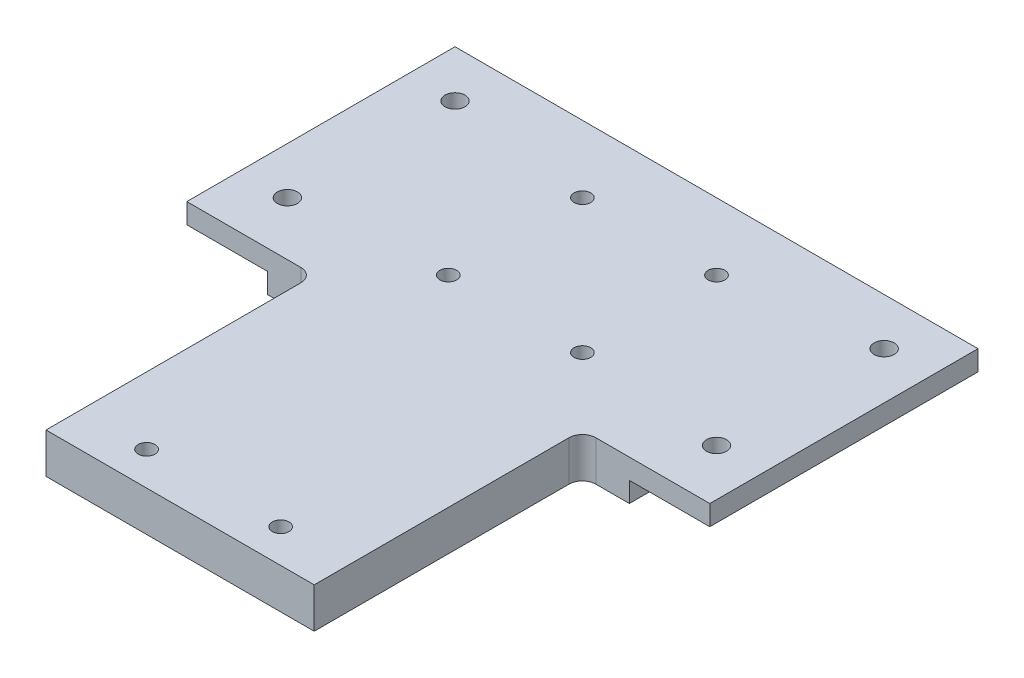
SolidWorks part; units mm, degrees
material "AISI 1045 钢，冷拔"
ref_plane "前视基准面" through (0, 0, 0) normal (0, 0, 1) x (1, 0, 0)
ref_plane "上视基准面" through (0, 0, 0) normal (0, 1, 0) x (1, 0, 0)
ref_plane "右视基准面" through (0, 0, 0) normal (1, 0, 0) x (0, 0, -1)
sketch "草图1" plane through (0, 0, 0) normal (0, 1, 0) x (1, 0, 0)
  line L0 (20, 0) -> (20, 82) construction
  line L1 (0, 0) -> (40, 0)
  line L7 (-19, 80) -> (-19, 40)
  line L8 (-19, 40) -> (0, 40)
  line L9 (0, 40) -> (0, 0)
  line L12 (59, 80) -> (59, 40)
  line L13 (59, 40) -> (40, 40)
  line L14 (40, 40) -> (40, 0)
  line L15 (-19, 80) -> (59, 80)
  dimension "D3" = 80
  dimension "D1" = 40
  dimension "D2" = 78
  dimension "D9" = 40
extrude "凸台-拉伸1" add sketch "草图1" along normal blind 6
fillet "圆角1" radius 2 2 edges at (0, 3, -40) (40, 3, -40)
sketch "草图18" plane through (0, 0, 0) normal (0, -1, 0) x (1, 0, 0)
  line L0 (-19, -40) -> (-7, -40)
  line L1 (-19, -40) -> (-2, -40) construction
  line L2 (-7, -40) -> (-7, -80)
  line L3 (59, -80) -> (-19, -80) construction
  line L4 (-7, -80) -> (-19, -80)
  line L5 (-19, -80) -> (-19, -40)
  line L6 (20, -80) -> (20, -16.0462) construction
  line L7 (47, -80) -> (59, -80)
  line L8 (59, -80) -> (59, -40)
  line L9 (59, -40) -> (47, -40)
  line L10 (47, -40) -> (47, -80)
  dimension "D1" = 12
extrude "切除-拉伸7" cut sketch "草图18" against normal blind 3
sketch "草图19" plane through (0, 3, 0) normal (0, -1, 0) x (1, 0, 0)
  line L0 (-19, -80) -> (-7, -80) construction
  line L1 (-19, -40) -> (-19, -80) construction
  line L2 (20, -91.1529) -> (20, -9.167) construction
  circle A0 centre (-12, -48) radius 1.5
  circle A1 centre (-12, -73) radius 1.5
  circle A2 centre (52, -73) radius 1.5
  circle A3 centre (52, -48) radius 1.5
  point P11 (30.8615, -109.7871)
  dimension "D2" = 3
  dimension "D1" = 7
  dimension "D3" = 25
  dimension "D4" = 7
  dimension "D5" = 39
extrude "切除-拉伸8" cut sketch "草图19" against normal blind 10
sketch "草图20" plane through (0, 0, 0) normal (0, -1, 0) x (1, 0, 0)
  line L0 (20, 0) -> (20, -11.5789) construction
  line L1 (0, 0) -> (40, 0) construction
  line L2 (47, -80) -> (-7, -80) construction
  circle A0 centre (10, -5) radius 1.25
  circle A1 centre (30, -5) radius 1.25
  circle A2 centre (10, -50) radius 1.25
  circle A3 centre (10, -70) radius 1.25
  circle A4 centre (30, -50) radius 1.25
  circle A5 centre (30, -70) radius 1.25
  dimension "D2" = 2.5
  dimension "D4" = 20
  dimension "D1" = 20
  dimension "D3" = 5
  dimension "D5" = 20
  dimension "D6" = 10
extrude "切除-拉伸9" cut sketch "草图20" against normal blind 10
